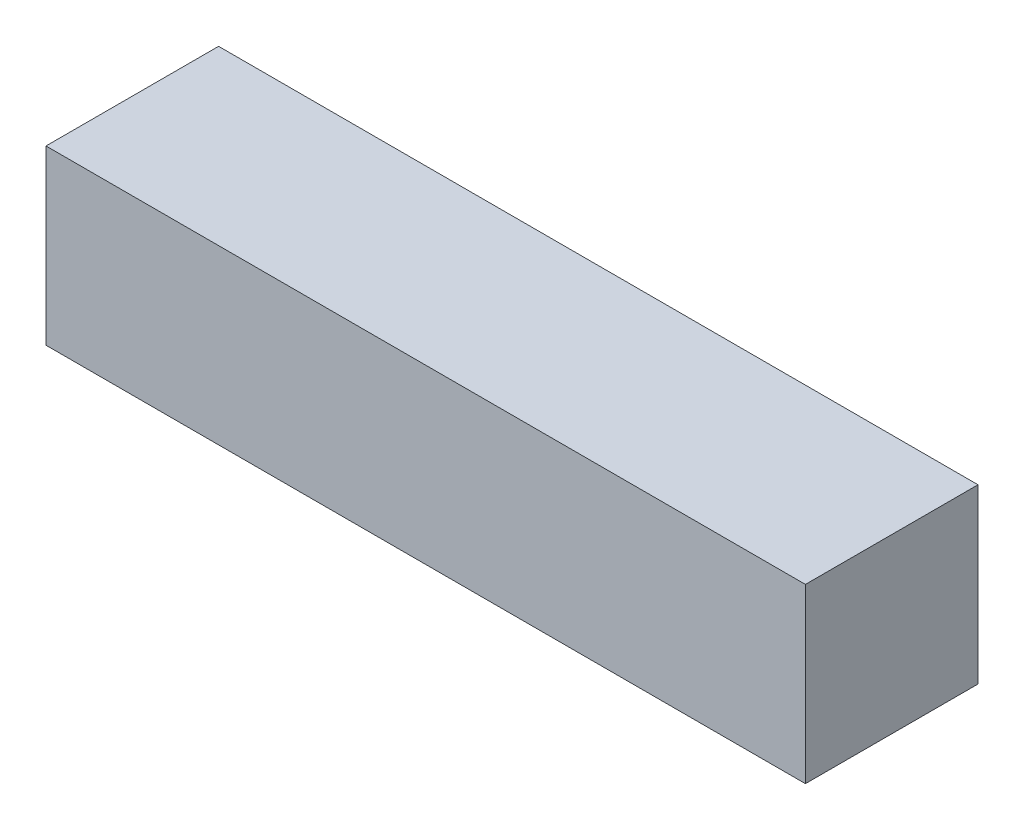
SolidWorks part; units mm, degrees
ref_plane "Plan de face" through (0, 0, 0) normal (0, 0, 1) x (1, 0, 0)
ref_plane "Plan de dessus" through (0, 0, 0) normal (0, 1, 0) x (1, 0, 0)
ref_plane "Plan de droite" through (0, 0, 0) normal (1, 0, 0) x (0, 0, -1)
sketch "Esquisse1" plane through (0, 0, 0) normal (0, 0, 1) x (1, 0, 0)
  line L1 (-17.6237, 12.9181) -> (4.3763, 12.9181)
  line L2 (-17.6237, 12.9181) -> (-17.6237, 7.9181)
  line L3 (-17.6237, 7.9181) -> (4.3763, 7.9181)
  line L4 (4.3763, 12.9181) -> (4.3763, 7.9181)
  dimension "D1" = 22
  dimension "D2" = 5
extrude "Boss.-Extru.2" add sketch "Esquisse1" along normal blind 5
